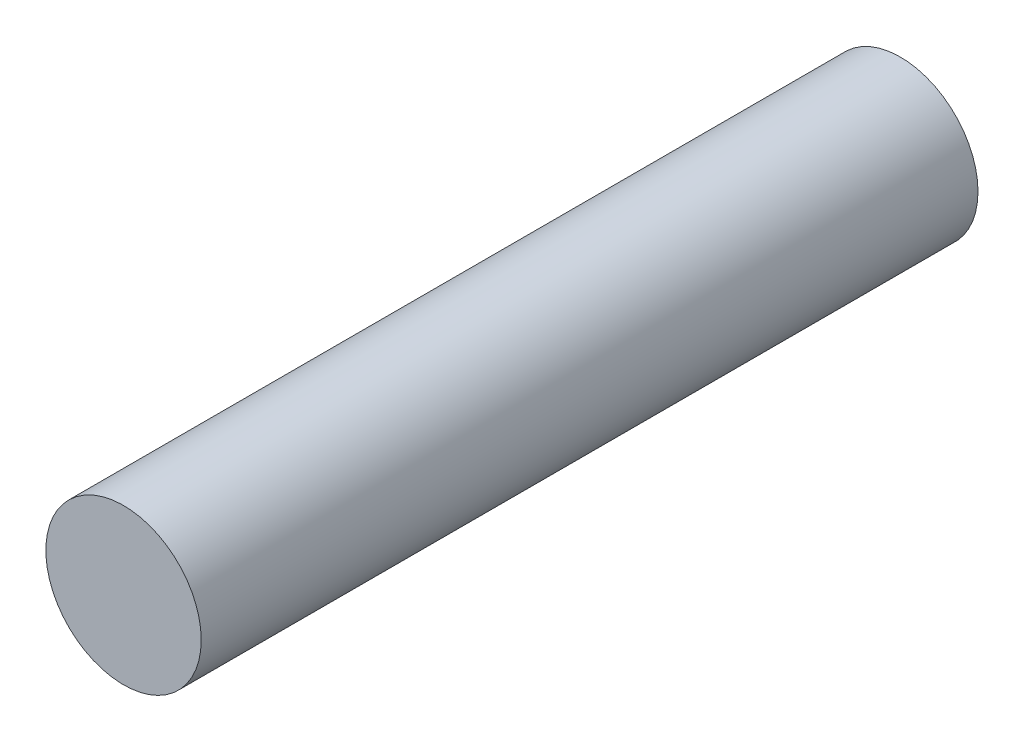
SolidWorks part; units mm, degrees
ref_plane "Front Plane" through (0, 0, 0) normal (0, 0, 1) x (1, 0, 0)
ref_plane "Top Plane" through (0, 0, 0) normal (0, 1, 0) x (1, 0, 0)
ref_plane "Right Plane" through (0, 0, 0) normal (1, 0, 0) x (0, 0, -1)
sketch "Cross Section Sketch" plane through (0, 0, 0) normal (0, 0, 1) x (1, 0, 0)
  circle A0 centre (0, 0) radius 7.5
  dimension "D1" = 15
extrude "Cross Section Extrude" add sketch "Cross Section Sketch" along normal blind 75
